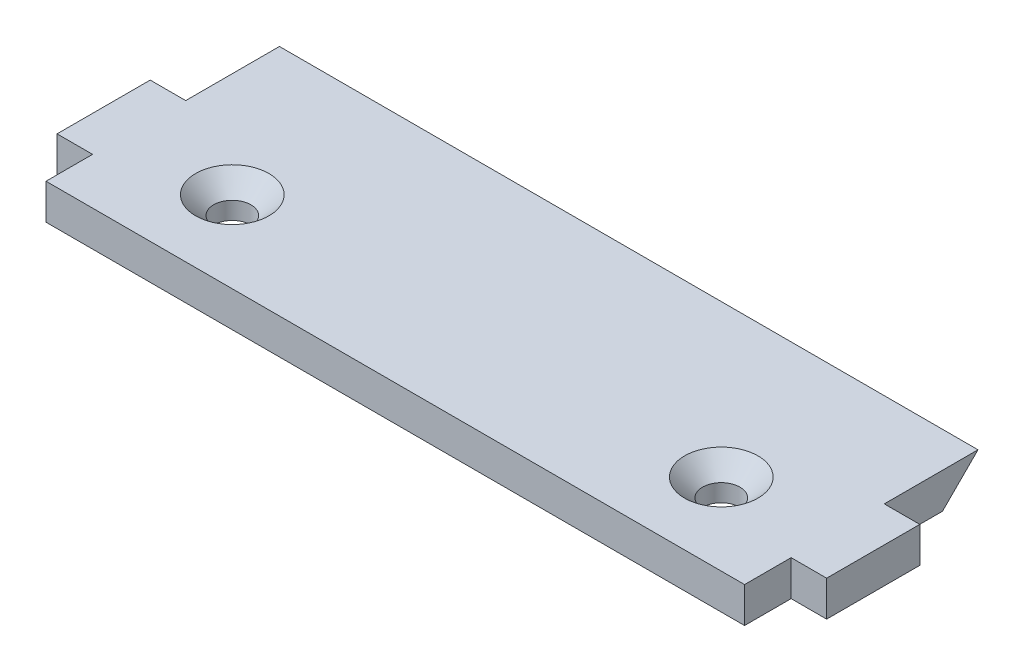
SolidWorks part; units mm, degrees
ref_plane "Front Plane" through (0, 0, 0) normal (0, 0, 1) x (1, 0, 0)
ref_plane "Top Plane" through (0, 0, 0) normal (0, 1, 0) x (1, 0, 0)
ref_plane "Right Plane" through (0, 0, 0) normal (1, 0, 0) x (0, 0, -1)
sketch "Sketch1" plane through (0, 0, 0) normal (0, 1, 0) x (1, 0, 0)
  line L0 (3.05, 12) -> (0, 7)
  line L1 (0, 0) -> (66.1, 0)
  line L2 (0, 0) -> (0, 20.05)
  line L3 (0, 20.05) -> (66.1, 20.05)
  line L4 (66.1, 0) -> (66.1, 20.05)
  line L7 (0, 12) -> (3.05, 12)
  line L8 (3.05, 20.05) -> (3.05, 12)
  line L11 (66.1, 12) -> (63.05, 12)
  line L12 (63.05, 20.05) -> (63.05, 12)
  line L13 (0, 0) -> (12.05, 0)
  line L14 (0, 0) -> (0, 7)
  line L15 (0, 7) -> (12.05, 7)
  line L16 (12.05, 0) -> (12.05, 7)
  line L17 (66.1, 0) -> (54.05, 0)
  line L18 (66.1, 0) -> (66.1, 7)
  line L19 (66.1, 7) -> (54.05, 7)
  line L20 (54.05, 0) -> (54.05, 7)
  line L21 (63.05, 12) -> (66.1, 7)
  line L23 (66.1, 0) -> (63.05, 0)
  line L24 (66.1, 0) -> (66.1, 4)
  line L25 (66.1, 4) -> (63.05, 4)
  line L26 (63.05, 0) -> (63.05, 4)
  line L27 (0, 0) -> (3.05, 0)
  line L28 (0, 0) -> (0, 4)
  line L29 (0, 4) -> (3.05, 4)
  line L30 (3.05, 0) -> (3.05, 4)
  circle A0 centre (12.05, 7) radius 1.5
  circle A1 centre (54.05, 7) radius 1.5
  dimension "D9" = 3
  dimension "D12" = 3
  dimension "D1" = 20.05
  dimension "D2" = 66.1
  dimension "D4" = 3.05
  dimension "D6" = 3.05
  dimension "D7" = 12.05
  dimension "D8" = 7
  dimension "D10" = 7
  dimension "D11" = 12.05
  dimension "D13" = 5
  dimension "D14" = 58.617
  dimension "D15" = 5
  dimension "D16" = 58.617
  dimension "D17" = 4
  dimension "D18" = 3.05
  dimension "D19" = 4
  dimension "D20" = 3.05
extrude "Boss-Extrude1" add sketch "Sketch1" along normal blind 3.05 contours L12 L3 L8 L7 L2 L1 L4 L11 | A0 L15 L2 L1 L16 | A1 L20 L1 L4 L19 | L11 L21 L4 | L7 L2 L0
hole_wizard "CSK for M3 Flat Head Machine Screw1" positions "Sketch4" profile "Sketch5" countersink size "M3" standard "ANSI Metric" end condition through all
sketch "Sketch4" plane through (0, 3.05, 0) normal (0, 1, 0) x (1, 0, 0)
  point P0 (12.05, 7)
sketch "Sketch5" plane through (12.05, 3.05, -7) normal (1, 0, 0) x (0, 0, 1)
  line L0 (0, 0) -> (0, 3.05)
  line L1 (0, 3.05) -> (1.6, 3.05)
  line L2 (1.6, 3.05) -> (1.6, 1.55)
  line L3 (1.6, 1.55) -> (3.15, 0)
  line L5 (3.15, 0) -> (0, 0)
  line L6 (-1.6, 1.55) -> (-3.15, 0) construction
  line L11 (0, -6.35) -> (0, 107.95) construction
  dimension "Thru Hole Dia." = 3.2
  dimension "Thru Hole Depth" = 3.05
  dimension "Near C'Sink Dia." = 6.3
  dimension "Near C'Sink Angle" = 90
hole_wizard "CSK for M3 Flat Head Machine Screw2" positions "Sketch6" profile "Sketch7" countersink size "M3" standard "ANSI Metric" end condition through all
sketch "Sketch6" plane through (0, 3.05, 0) normal (0, 1, 0) x (1, 0, 0)
  point P0 (54.05, 7)
sketch "Sketch7" plane through (54.05, 3.05, -7) normal (1, 0, 0) x (0, 0, 1)
  line L0 (0, 0) -> (0, 3.05)
  line L1 (0, 3.05) -> (1.6, 3.05)
  line L2 (1.6, 3.05) -> (1.6, 1.55)
  line L3 (1.6, 1.55) -> (3.15, 0)
  line L5 (3.15, 0) -> (0, 0)
  line L6 (-1.6, 1.55) -> (-3.15, 0) construction
  line L11 (0, -6.35) -> (0, 107.95) construction
  dimension "Thru Hole Dia." = 3.2
  dimension "Thru Hole Depth" = 3.05
  dimension "Near C'Sink Dia." = 6.3
  dimension "Near C'Sink Angle" = 90
sketch "Sketch8" plane through (63.05, 0, 0) normal (1, 0, 0) x (0, 0, -1)
  line L0 (20.05, 3.05) -> (17, 0)
  line L1 (20.05, 0) -> (12, 0) construction
  line L2 (17, 0) -> (20.05, 0)
  line L3 (20.05, 0) -> (20.05, 3.05)
  dimension "D1" = 45
extrude "Cut-Extrude1" cut sketch "Sketch8" against normal through all
